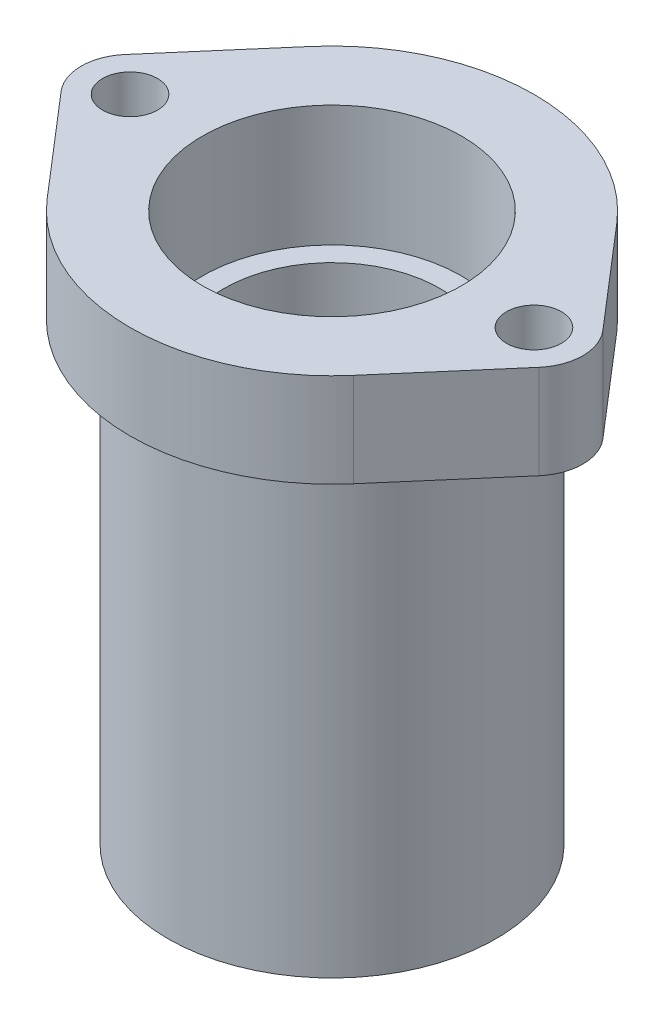
SolidWorks part; units mm, degrees
ref_plane "Front Plane" through (0, 0, 0) normal (0, 0, 1) x (1, 0, 0)
ref_plane "Top Plane" through (0, 0, 0) normal (0, 1, 0) x (1, 0, 0)
ref_plane "Right Plane" through (0, 0, 0) normal (1, 0, 0) x (0, 0, -1)
sketch "Sketch1" plane through (0, 0, 0) normal (0, 1, 0) x (1, 0, 0)
  line L0 (-15.0296, 2.0046) -> (-9.6266, 8.2836)
  line L1 (9.6266, 8.2836) -> (15.0296, 2.0046)
  line L2 (-15.0296, -2.0046) -> (-9.6266, -8.2836)
  line L3 (15.0296, -2.0046) -> (9.6266, -8.2836)
  line L5 (-55, 0) -> (55, 0) construction
  circle A0 centre (0, 0) radius 8.1661 construction
  arc A1 (-9.6266, -8.2836) -> (9.6266, -8.2836) centre (0, 0) ccw
  circle A2 centre (-12.7, 0) radius 1.7272
  circle A3 centre (12.7, 0) radius 1.7272
  arc A4 (-15.0296, 2.0046) -> (-15.0296, -2.0046) centre (-12.7, 0) ccw
  arc A5 (15.0296, -2.0046) -> (15.0296, 2.0046) centre (12.7, 0) ccw
  arc A6 (9.6266, 8.2836) -> (-9.6266, 8.2836) centre (0, 0) ccw
  point P10 (0, 0)
  point P22 (0, 0)
  point P23 (0, 0)
  dimension "D1" = 16.3322
  dimension "D2" = 25.4
  dimension "D3" = 6.1468
  dimension "D4" = 3.4544
extrude "Boss-Extrude1" add sketch "Sketch1" along normal blind 5.9055
sketch "Sketch2" plane through (0, 0, 0) normal (0, -1, 0) x (1, 0, 0)
  circle A0 centre (0, 0) radius 10.3187
  dimension "D1" = 20.6375
extrude "Boss-Extrude2" add sketch "Sketch2" along normal blind 28.575
sketch "Sketch3" plane through (0, 5.9055, 0) normal (0, 1, 0) x (1, 0, 0)
  circle A0 centre (0, 0) radius 8.1534
  dimension "D1" = 16.3068
extrude "Cut-Extrude1" cut sketch "Sketch3" against normal blind 7.62
sketch "Sketch4" plane through (0, 5.9055, 0) normal (0, 1, 0) x (1, 0, 0)
  circle A0 centre (0, 0) radius 6.7945
  dimension "D1" = 13.589
extrude "Cut-Extrude2" cut sketch "Sketch4" against normal blind 16.256
sketch "Sketch5" plane through (0, 5.9055, 0) normal (0, 1, 0) x (1, 0, 0)
  circle A0 centre (0, 0) radius 5.08
  dimension "D1" = 10.16
extrude "Cut-Extrude3" cut sketch "Sketch5" against normal through all
